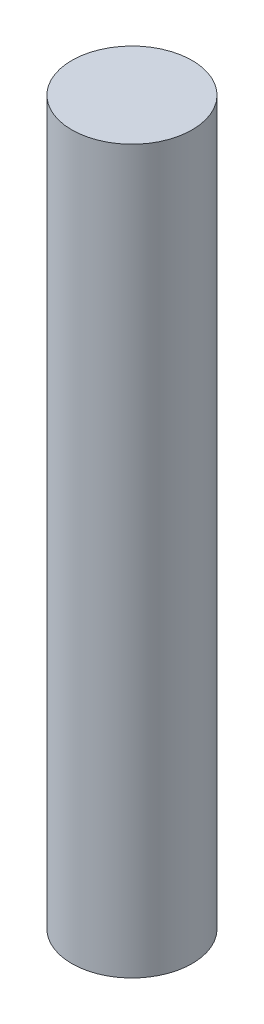
SolidWorks part; units mm, degrees
ref_plane "Front Plane" through (0, 0, 0) normal (0, 0, 1) x (1, 0, 0)
ref_plane "Top Plane" through (0, 0, 0) normal (0, 1, 0) x (1, 0, 0)
ref_plane "Right Plane" through (0, 0, 0) normal (1, 0, 0) x (0, 0, -1)
sketch "Sketch1" plane through (0, 0, 0) normal (0, 1, 0) x (1, 0, 0)
  circle A0 centre (0, 0) radius 4
  dimension "D1" = 8
extrude "Boss-Extrude1" add sketch "Sketch1" along normal blind 48 contours A0
